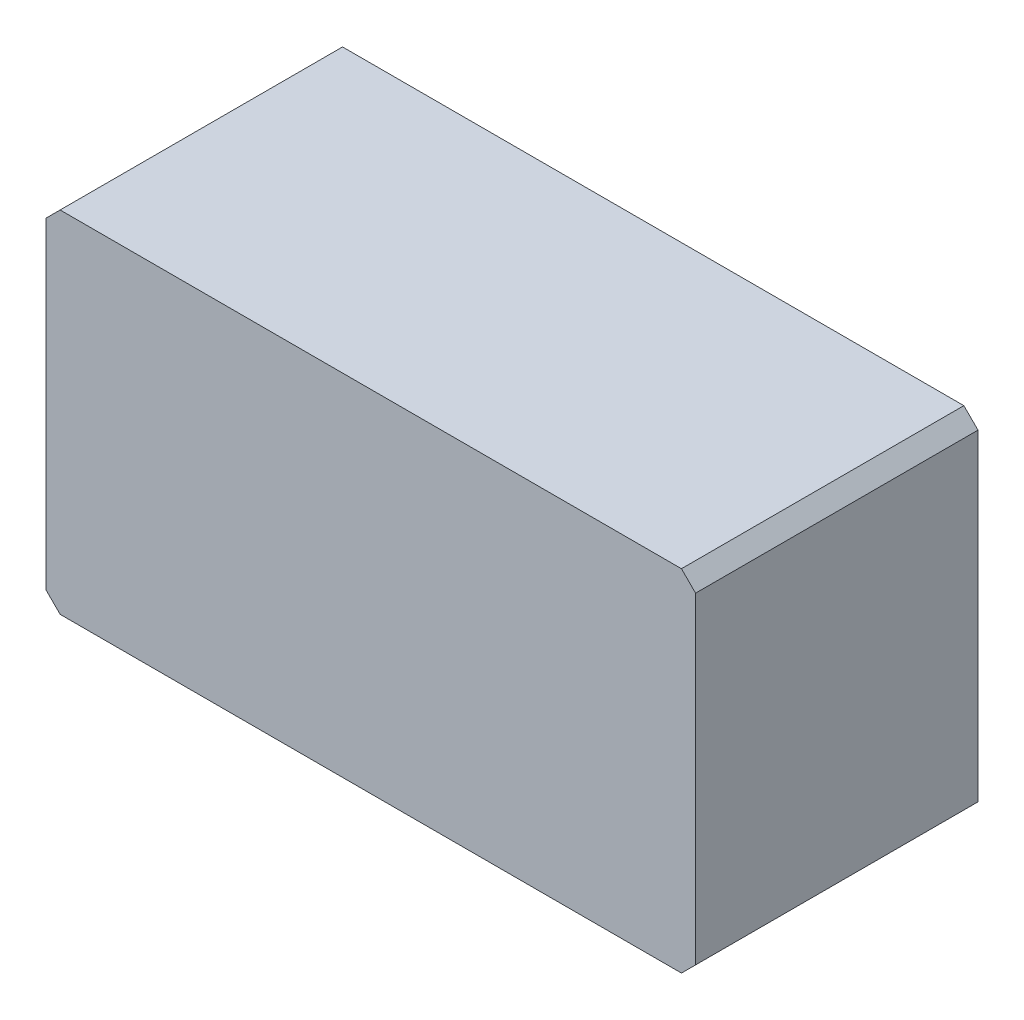
SolidWorks part; units mm, degrees
ref_plane "前视基准面" through (0, 0, 0) normal (0, 0, 1) x (1, 0, 0)
ref_plane "上视基准面" through (0, 0, 0) normal (0, 1, 0) x (1, 0, 0)
ref_plane "右视基准面" through (0, 0, 0) normal (1, 0, 0) x (0, 0, -1)
sketch "草图1" plane through (0, 0, 0) normal (0, 0, 1) x (1, 0, 0)
  line L0 (0.55, 0.31) -> (0.575, 0.285)
  line L1 (0.575, 0.285) -> (0.575, -0.285)
  line L2 (0.575, -0.285) -> (0.55, -0.31)
  line L3 (0.55, -0.31) -> (-0.55, -0.31)
  line L4 (-0.55, -0.31) -> (-0.575, -0.285)
  line L5 (-0.575, -0.285) -> (-0.575, 0.285)
  line L6 (-0.575, 0.285) -> (-0.55, 0.31)
  line L7 (-0.55, 0.31) -> (0.55, 0.31)
extrude "Component_Outline" add sketch "草图1" along normal blind 0.5 separate body
sketch3d "3D草图1"
  line L0 (0, 0, 0) -> (1, 0, 0)
  line L1 (0, 0, 0) -> (0, 1, 0)
  line L2 (0, 0, 0) -> (0, 0, 1)
  point P0 (0, 0, 0)
